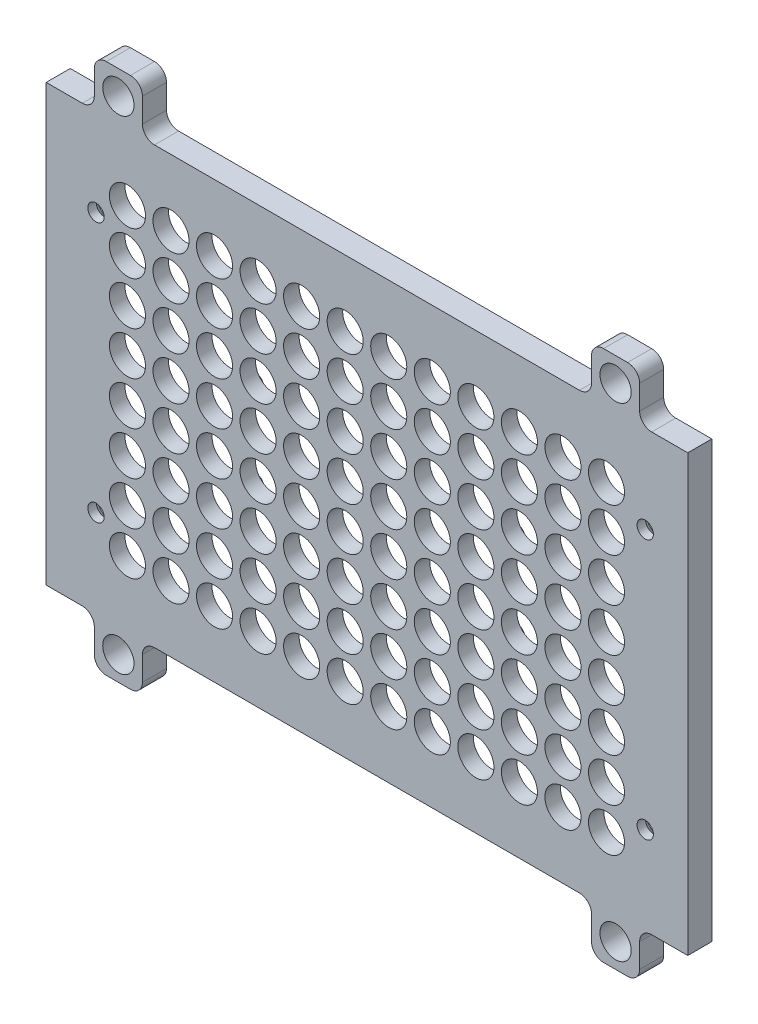
SolidWorks part; units mm, degrees
ref_plane "Front Plane" through (0, 0, 0) normal (0, 0, 1) x (1, 0, 0)
ref_plane "Top Plane" through (0, 0, 0) normal (0, 1, 0) x (1, 0, 0)
ref_plane "Right Plane" through (0, 0, 0) normal (1, 0, 0) x (0, 0, -1)
sketch "Sketch1" plane through (0, 0, 0) normal (0, 0, 1) x (1, 0, 0)
  line L1 (-56.2249, 73.01) -> (77.0697, 73.01)
  line L2 (-56.2249, 73.01) -> (-56.2249, -17.44)
  line L3 (-56.2249, -17.44) -> (77.0697, -17.44)
  line L4 (77.0697, 73.01) -> (77.0697, -17.44)
  dimension "D1" = 133.2946
  dimension "D2" = 90.45
extrude "Boss-Extrude1" add sketch "Sketch1" along normal blind 5
sketch "Sketch2" plane through (0, 0, 0) normal (0, 0, -1) x (-1, 0, 0)
  line L0 (54.2249, -17.44) -> (54.2249, -15.44) construction
  line L1 (56.2249, -17.44) -> (-77.0697, -17.44) construction
  line L2 (54.2249, -15.44) -> (56.2249, -15.44) construction
  line L3 (56.2249, 73.01) -> (56.2249, -17.44) construction
  line L4 (-75.0697, -15.44) -> (-77.0697, -15.44) construction
  line L5 (54.2249, -15.44) -> (-75.0697, -15.44)
  line L6 (54.2249, -15.44) -> (54.2249, 71.01)
  line L7 (54.2249, 71.01) -> (-75.0697, 71.01)
  line L8 (-75.0697, -15.44) -> (-75.0697, 71.01)
  line L9 (-77.0697, -17.44) -> (-77.0697, 73.01) construction
  line L10 (-75.0697, 71.01) -> (-75.0697, 73.01) construction
  line L11 (-77.0697, 73.01) -> (56.2249, 73.01) construction
  line L12 (-75.0697, 71.01) -> (-71.1947, 71.01) construction
  line L13 (54.2249, -11.59) -> (50.3499, -11.59) construction
  line L14 (50.3499, -11.59) -> (50.3499, -15.44) construction
  line L15 (-71.1947, 71.01) -> (-71.1947, 67.16) construction
  line L17 (50.3499, -11.59) -> (-71.1947, -11.59)
  line L18 (50.3499, -11.59) -> (50.3499, 67.16)
  line L19 (50.3499, 67.16) -> (-71.1947, 67.16)
  line L20 (-71.1947, -11.59) -> (-71.1947, 67.16)
  dimension "D1" = 2
  dimension "D2" = 2
  dimension "D3" = 86.45
  dimension "D4" = 129.2946
  dimension "D5" = 2
  dimension "D6" = 2
  dimension "D7" = 3.875
  dimension "D8" = 3.875
  dimension "D9" = 3.85
  dimension "D10" = 3.85
extrude "Cut-Extrude1" cut sketch "Sketch2" against normal blind 4.5
sketch "Sketch3" plane through (0, 0, 0) normal (0, 0, -1) x (-1, 0, 0)
  line L3 (56.2249, -3.715) -> (39.3426, -3.715) construction
  line L4 (56.2249, 73.01) -> (56.2249, -17.44) construction
  line L5 (39.3426, -17.44) -> (39.3426, -3.715) construction
  line L6 (56.2249, -17.44) -> (-77.0697, -17.44) construction
  circle A0 centre (39.3426, -3.715) radius 3.75
  dimension "D3" = 7.5
  dimension "D1" = 16.8823
  dimension "D2" = 13.725
extrude "Cut-Extrude5" cut sketch "Sketch3" against normal blind 10
pattern_linear "LPattern1" count 8 spacing 9 along (0, 1, 0) count 12 spacing 9.0482 along (1, 0, 0) of "Cut-Extrude5"
sketch "Sketch8" plane through (0, 0, 0) normal (0, 0, -1) x (-1, 0, 0)
  line L1 (50.3499, -11.59) -> (-71.1947, -11.59)
  line L2 (50.3499, -11.59) -> (50.3499, 67.16)
  line L3 (50.3499, 67.16) -> (-71.1947, 67.16)
  line L4 (-71.1947, -11.59) -> (-71.1947, 67.16)
extrude "Cut-Extrude8" cut sketch "Sketch8" against normal blind 1.77
fillet "Fillet4" radius 4.15 4 edges at (75.0697, -15.44, 2.25) (75.0697, 71.01, 2.25) (-54.2249, 71.01, 2.25) (-54.2249, -15.44, 2.25)
fillet "Fillet5" radius 2.3 4 edges at (71.1947, -11.59, 3.135) (71.1947, 67.16, 3.135) (-50.3499, 67.16, 3.135) (-50.3499, -11.59, 3.135)
sketch "Sketch10" plane through (0, 0, 5) normal (0, 0, 1) x (1, 0, 0)
  line L0 (68.2301, 73.01) -> (68.2301, 54.78) construction
  line L1 (77.0697, 73.01) -> (-56.2249, 73.01) construction
  line L2 (77.0697, 54.78) -> (68.2301, 54.78) construction
  line L3 (77.0697, -17.44) -> (77.0697, 73.01) construction
  line L4 (-45.8774, 73.01) -> (-45.8774, 54.78) construction
  line L5 (-39.3426, -3.715) -> (-45.8774, -3.715) construction
  line L6 (-56.2249, 73.01) -> (-56.2249, -17.44) construction
  line L7 (-56.2249, 0.79) -> (-45.8774, 0.79) construction
  line L8 (-45.8774, -17.44) -> (-45.8774, 0.79) construction
  line L9 (-56.2249, -17.44) -> (77.0697, -17.44) construction
  line L10 (77.0697, 0.79) -> (68.2301, 0.79) construction
  line L11 (68.2301, 0.79) -> (68.2301, -17.44) construction
  line L12 (60.1873, -3.715) -> (68.2301, -3.715) construction
  line L13 (68.2301, -3.715) -> (68.2301, 0.79) construction
  line L14 (60.1873, 59.285) -> (68.2301, 59.285) construction
  line L15 (-39.3426, 59.285) -> (-45.8774, 59.285) construction
  line L16 (-45.8774, 54.78) -> (-56.2249, 54.78) construction
  line L17 (-45.8774, 54.78) -> (68.2301, 54.78) construction
  circle A0 centre (68.2301, 54.78) radius 0.95
  circle A1 centre (68.2301, 0.79) radius 0.95
  circle A2 centre (-45.8774, 0.79) radius 0.95
  circle A3 centre (-45.8774, 54.78) radius 0.95
  dimension "D5" = 6.5348
  dimension "D7" = 1.9
  dimension "D8" = 1.9
  dimension "D9" = 1.9
  dimension "D10" = 1.9
  dimension "D1" = 18.23
  dimension "D2" = 8.0428
  dimension "D3" = 6.5348
  dimension "D4" = 18.23
  dimension "D6" = 8.0428
  dimension "D11" = 8.8395
  dimension "D12" = 10.3475
  dimension "D13" = 114.1076
extrude "Cut-Extrude10" cut sketch "Sketch10" against normal blind 10
sketch "Sketch14" plane through (0, 0, 1.77) normal (0, 0, -1) x (-1, 0, 0)
  line L0 (-33.0428, 32.285) -> (-42.091, 41.285) construction
  line L1 (-42.091, 32.285) -> (-33.0428, 41.285) construction
  line L2 (21.2463, 41.285) -> (12.1981, 32.285) construction
  line L3 (21.2463, 14.285) -> (12.1981, 23.285) construction
  line L4 (-42.091, 14.285) -> (-33.0428, 23.285) construction
  circle A0 centre (-37.5669, 36.785) radius 1.4
  circle A1 centre (-37.5669, 18.785) radius 1.4
  circle A2 centre (16.7222, 36.785) radius 1.4
  circle A3 centre (16.7222, 18.785) radius 1.4
  dimension "D1" = 2.8
  dimension "D2" = 2.8
  dimension "D3" = 2.8
  dimension "D4" = 2.8
extrude "Boss-Extrude3" add sketch "Sketch14" along normal blind 1
sketch "Sketch17" plane through (0, 0, 0) normal (0, 0, -1) x (-1, 0, 0)
  line L0 (-77.0697, -17.44) -> (-67.0697, -17.44) construction
  line L1 (56.2249, -17.44) -> (-77.0697, -17.44) construction
  line L2 (-77.0697, 73.01) -> (56.2249, 73.01) construction
  line L3 (-67.0697, -17.44) -> (-57.0697, -17.44)
  line L4 (-67.0697, -17.44) -> (-67.0697, -27.44)
  line L5 (-67.0697, -27.44) -> (-57.0697, -27.44)
  line L6 (-57.0697, -17.44) -> (-57.0697, -27.44)
  line L7 (-67.0697, 73.01) -> (-57.0697, 73.01)
  line L8 (-67.0697, 73.01) -> (-67.0697, 83.01)
  line L9 (-67.0697, 83.01) -> (-57.0697, 83.01)
  line L10 (-57.0697, 73.01) -> (-57.0697, 83.01)
  line L11 (56.2249, -17.44) -> (46.2249, -17.44) construction
  line L12 (-77.0697, 73.01) -> (-67.0697, 73.01) construction
  line L13 (46.2249, -17.44) -> (36.2249, -17.44)
  line L14 (46.2249, -17.44) -> (46.2249, -27.44)
  line L15 (46.2249, -27.44) -> (36.2249, -27.44)
  line L16 (36.2249, -17.44) -> (36.2249, -27.44)
  line L17 (36.2249, 73.01) -> (46.2249, 73.01)
  line L18 (36.2249, 73.01) -> (36.2249, 83.01)
  line L19 (36.2249, 83.01) -> (46.2249, 83.01)
  line L20 (46.2249, 73.01) -> (46.2249, 83.01)
  line L21 (46.2249, 73.01) -> (56.2249, 73.01) construction
  line L22 (36.2249, -17.44) -> (-57.0697, -17.44) construction
  line L23 (56.2249, -17.44) -> (46.2249, -17.44) construction
  line L24 (45.8774, 0.79) -> (45.8774, -15.44) construction
  line L25 (-70.9197, -15.44) -> (50.0749, -15.44) construction
  line L26 (46.2249, -15.44) -> (45.8774, -15.44) construction
  line L27 (-68.2301, 0.79) -> (-68.2301, -15.44) construction
  line L28 (-68.2301, -15.44) -> (-67.0697, -15.44) construction
  dimension "D1" = 10
  dimension "D2" = 10
  dimension "D3" = 10
  dimension "D4" = 10
  dimension "D5" = 10
  dimension "D6" = 10
  dimension "D7" = 10
  dimension "D8" = 10
  dimension "D9" = 10
  dimension "D10" = 10
  dimension "D11" = 10
  dimension "D12" = 93.2946
  dimension "D13" = 0.3475
  dimension "D14" = 1.1605
extrude "Boss-Extrude4" add sketch "Sketch17" against normal blind 5
sketch "Sketch18" plane through (0, 0, 0) normal (0, 0, -1) x (-1, 0, 0)
  line L0 (-67.0697, -17.44) -> (-57.0697, -27.44) construction
  line L1 (36.2249, -17.44) -> (46.2249, -27.44) construction
  line L2 (36.2249, 83.01) -> (46.2249, 73.01) construction
  line L3 (-67.0697, 83.01) -> (-57.0697, 73.01) construction
  circle A0 centre (-62.0697, -22.44) radius 3.25
  circle A1 centre (-62.0697, 78.01) radius 3.25
  circle A2 centre (41.2249, 78.01) radius 3.25
  circle A3 centre (41.2249, -22.44) radius 3.25
  dimension "D1" = 6.5
  dimension "D2" = 6.5
  dimension "D3" = 6.5
  dimension "D4" = 6.5
extrude "Cut-Extrude13" cut sketch "Sketch18" against normal blind 5
fillet "Fillet6" radius 2.5 16 edges at (-36.2249, -17.44, 2.5) (-46.2249, -17.44, 2.5) (-36.2249, 73.01, 2.5) (-46.2249, 73.01, 2.5) (67.0697, 83.01, 2.5) (57.0697, 83.01, 2.5) (-36.2249, 83.01, 2.5) (-46.2249, 83.01, 2.5) (67.0697, -27.44, 2.5) (57.0697, -27.44, 2.5) (-36.2249, -27.44, 2.5) (-46.2249, -27.44, 2.5)
sketch "Sketch21" plane through (0, 0, 0) normal (0, 0, -1) x (-1, 0, 0)
  line L0 (-77.0697, -17.44) -> (-73.8542, -14.2244) construction
  arc A0 (-75.0697, -11.29) -> (-70.9197, -15.44) centre (-70.9197, -11.29) ccw construction
  circle A1 centre (-75.4619, -15.8322) radius 1
  dimension "D1" = 2
extrude "Cut-Extrude15" cut sketch "Sketch21" against normal blind 1
hole_wizard "CSK for M3 Flat Head Machine Screw1" positions "Sketch24" profile "Sketch23" countersink size "M3" standard "ANSI Metric" end condition through all
sketch "Sketch24" plane through (0, 0, 1.77) normal (0, 0, -1) x (-1, 0, 0)
  point P0 (45.8774, 0.79)
  point P3 (45.8774, 54.78)
  point P6 (-68.2301, 54.78)
  point P9 (-68.2301, 0.79)
sketch "Sketch23" plane through (-45.8774, 0.79, 1.77) normal (1, 0, 0) x (0, 1, 0)
  line L0 (0, 0) -> (0, 3.23)
  line L1 (0, 3.23) -> (1.7, 3.23)
  line L2 (1.7, 3.23) -> (1.7, 1.45)
  line L3 (1.7, 1.45) -> (3.15, 0)
  line L5 (3.15, 0) -> (0, 0)
  line L6 (-1.7, 1.45) -> (-3.15, 0) construction
  line L11 (0, -6.35) -> (0, 107.95) construction
  dimension "Thru Hole Dia." = 3.4
  dimension "Thru Hole Depth" = 3.23
  dimension "Near C'Sink Dia." = 6.3
  dimension "Near C'Sink Angle" = 90
